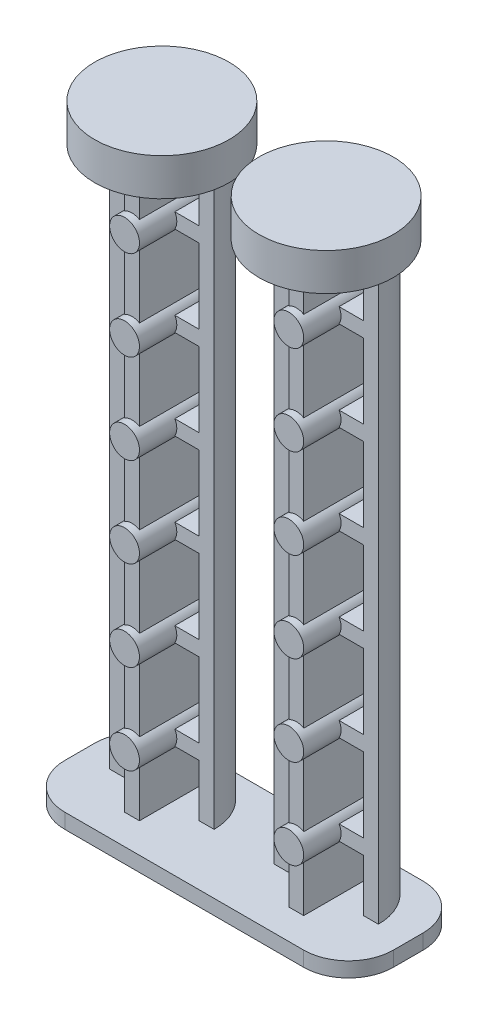
SolidWorks part; units mm, degrees
ref_plane "Front Plane" through (0, 0, 0) normal (0, 0, 1) x (1, 0, 0)
ref_plane "Top Plane" through (0, 0, 0) normal (0, 1, 0) x (1, 0, 0)
ref_plane "Right Plane" through (0, 0, 0) normal (1, 0, 0) x (0, 0, -1)
sketch "Sketch2" plane through (0, 0, 0) normal (0, 1, 0) x (1, 0, 0)
  line L0 (-11, 0) -> (0, 0) construction
  circle A0 centre (-11, 0) radius 9
  dimension "D1" = 18
  dimension "D2" = 11
extrude "Boss-Extrude1" add sketch "Sketch2" against normal blind 5
sketch "Sketch3" plane through (0, -5, 0) normal (0, -1, 0) x (1, 0, 0)
  line L0 (-4, 0) -> (-6, 0)
  line L1 (-16, 0) -> (-18, 0)
  arc A0 (-18, 0) -> (-4, 0) centre (-11, 0) ccw
  arc A1 (-16, 0) -> (-6, 0) centre (-11, 0) ccw
  dimension "D1" = 14
  dimension "D2" = 10
extrude "Boss-Extrude2" add sketch "Sketch3" along normal blind 76
ref_plane "Plane1" through (0, 0, 5) normal (0, 0, 1) x (1, 0, 0)
sketch "Sketch4" plane through (0, 0, 5) normal (0, 0, 1) x (1, 0, 0)
  line L0 (-16, -5) -> (-6, -5) construction
  line L1 (-11, 0) -> (-11, -13) construction
  line L2 (-2, 0) -> (-20, 0) construction
  line L3 (-16, -81) -> (-6, -81) construction
  circle A0 centre (-11, -13) radius 2
  circle A1 centre (-11, -25) radius 2
  circle A2 centre (-11, -37) radius 2
  circle A3 centre (-11, -49) radius 2
  circle A4 centre (-11, -61) radius 2
  circle A5 centre (-11, -73) radius 2
  dimension "D2" = 4
  dimension "D1" = 8
  dimension "D4" = 8
  dimension "D3" = 6
extrude "Boss-Extrude3" add sketch "Sketch4" against normal up to surface (9.5826 mm away)
sketch "Sketch5" plane through (0, -81, 0) normal (0, -1, 0) x (1, 0, 0)
  line L1 (16, 8) -> (-16, 8)
  line L2 (22, 2) -> (22, -2)
  line L3 (16, -8) -> (-16, -8)
  line L4 (-22, 2) -> (-22, -2)
  line L5 (22, 8) -> (-22, -8) construction
  line L6 (22, -8) -> (-22, 8) construction
  arc A0 (16, 8) -> (22, 2) centre (16, 2) cw
  arc A1 (22, -2) -> (16, -8) centre (16, -2) cw
  arc A2 (-16, -8) -> (-22, -2) centre (-16, -2) cw
  arc A3 (-16, 8) -> (-22, 2) centre (-16, 2) ccw
  point P0 (0, 0)
  dimension "D3" = 6
  dimension "D1" = 44
  dimension "D2" = 16
extrude "Boss-Extrude4" add sketch "Sketch5" along normal blind 2
ref_plane "Plane2" through (0, 0, 4) normal (0, 0, 1) x (1, 0, 0)
sketch "Sketch9" plane through (0, 0, 4) normal (0, 0, 1) x (1, 0, 0)
  line L0 (-11, -5) -> (-11, -11)
  line L1 (-16, -5) -> (-6, -5) construction
  line L2 (-11, -15) -> (-11, -23)
  line L3 (-11, -27) -> (-11, -35)
  line L4 (-11, -39) -> (-11, -47)
  line L5 (-11, -51) -> (-11, -59)
  line L6 (-11, -63) -> (-11, -71)
  line L7 (-11, -75) -> (-11, -81)
  line L8 (-6, -81) -> (-16, -81) construction
  circle A0 centre (-11, -13) radius 2 construction
  circle A1 centre (-11, -25) radius 2 construction
  circle A2 centre (-11, -37) radius 2 construction
  circle A3 centre (-11, -49) radius 2 construction
  circle A4 centre (-11, -49) radius 2 construction
  circle A5 centre (-11, -61) radius 2 construction
  circle A6 centre (-11, -73) radius 2 construction
  circle A7 centre (-11, -73) radius 2 construction
rib "Rib4" sketch "Sketch9" sketch "Sketch9" thickness 2 extrusion direction normal to sketch draft on no parameters "D1"=2
sketch "Sketch10" plane through (0, 0, 0) normal (0, 0, 1) x (1, 0, 0)
  line L0 (-13, -73) -> (-16, -73)
  line L1 (-16, -81) -> (-16, -5) construction
  line L2 (-9, -73) -> (-6, -73)
  line L3 (-6, -81) -> (-6, -5) construction
  line L4 (-13, -61) -> (-16, -61)
  line L5 (-9, -61) -> (-6, -61)
  line L6 (-13, -49) -> (-16, -49)
  line L7 (-9, -49) -> (-6, -49)
  line L8 (-13, -37) -> (-16, -37)
  line L9 (-9, -37) -> (-6, -37)
  line L10 (-13, -25) -> (-16, -25)
  line L11 (-9, -25) -> (-6, -25)
  line L12 (-13, -13) -> (-16, -13)
  line L13 (-9, -13) -> (-6, -13)
  arc A0 (-12, -71.2679) -> (-12, -74.7321) centre (-11, -73) ccw construction
  arc A1 (-10, -74.7321) -> (-10, -71.2679) centre (-11, -73) ccw construction
  arc A2 (-12, -59.2679) -> (-12, -62.7321) centre (-11, -61) ccw construction
  arc A3 (-10, -62.7321) -> (-10, -59.2679) centre (-11, -61) ccw construction
  arc A4 (-12, -47.2679) -> (-12, -50.7321) centre (-11, -49) ccw construction
  arc A5 (-10, -50.7321) -> (-10, -47.2679) centre (-11, -49) ccw construction
  arc A6 (-12, -35.2679) -> (-12, -38.7321) centre (-11, -37) ccw construction
  arc A7 (-10, -38.7321) -> (-10, -35.2679) centre (-11, -37) ccw construction
  arc A8 (-12, -23.2679) -> (-12, -26.7321) centre (-11, -25) ccw construction
  arc A9 (-10, -26.7321) -> (-10, -23.2679) centre (-11, -25) ccw construction
  arc A10 (-12, -11.2679) -> (-12, -14.7321) centre (-11, -13) ccw construction
  arc A11 (-10, -14.7321) -> (-10, -11.2679) centre (-11, -13) ccw construction
rib "Rib5" sketch "Sketch10" sketch "Sketch10" thickness 2 extrusion direction normal to sketch draft on no parameters "D1"=2
mirror "Mirror5" about plane through (0, 0, 0) normal (1, 0, 0) of bodies 104
